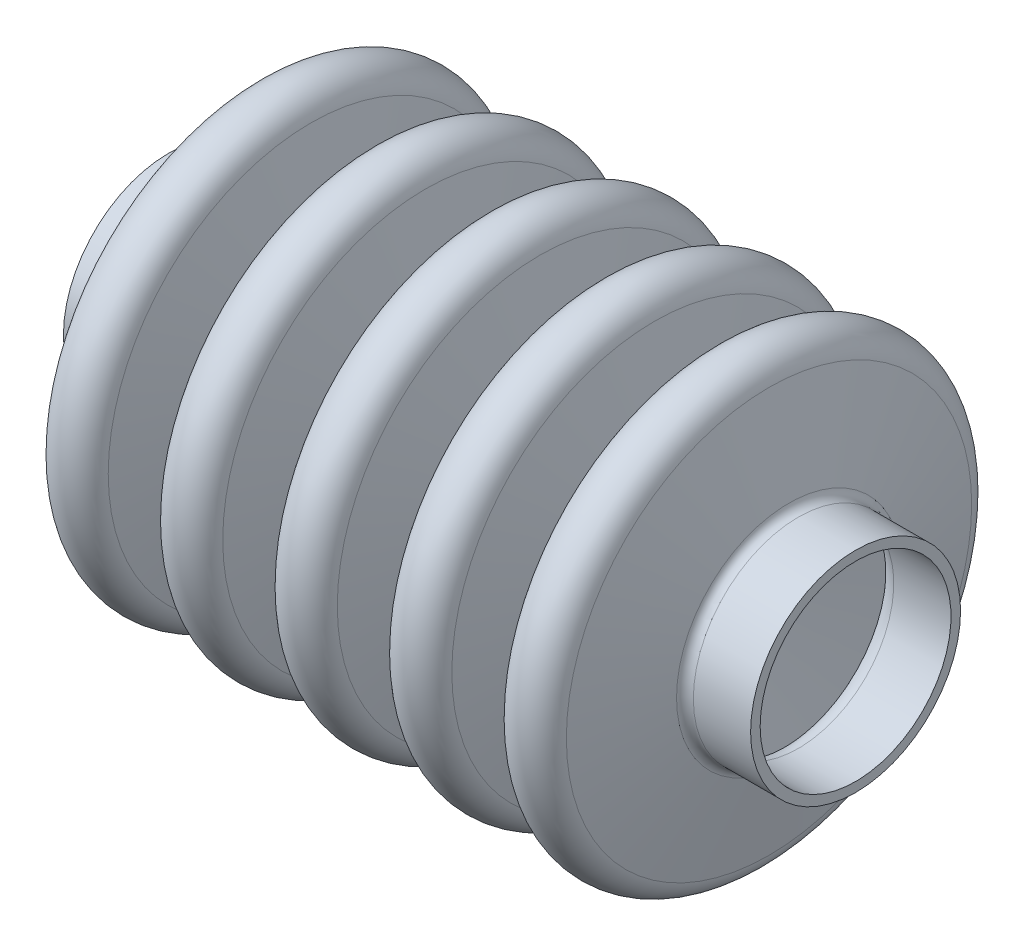
SolidWorks part; units mm, degrees
ref_plane "Front Plane" through (0, 0, 0) normal (0, 0, 1) x (1, 0, 0)
ref_plane "Top Plane" through (0, 0, 0) normal (0, 1, 0) x (1, 0, 0)
ref_plane "Right Plane" through (0, 0, 0) normal (1, 0, 0) x (0, 0, -1)
sketch "Sketch2" plane through (0, 0, 0) normal (0, 1, 0) x (1, 0, 0)
  line L0 (0, 0) -> (35.1605, 0) construction
  line L1 (0, 0) -> (0, 10) construction
  line L2 (0, 10) -> (-6, 10)
  line L3 (-12, 0) -> (-12, 10) construction
  line L4 (-7.9526, 11.5671) -> (-10.0474, 21.0162)
  line L5 (-16.0474, 11.5671) -> (-13.9526, 21.0162)
  line L6 (-19.9526, 11.5671) -> (-22.0474, 21.0162)
  line L7 (-28.0474, 11.5671) -> (-25.9526, 21.0162)
  line L8 (-31.9526, 11.5671) -> (-34.0474, 21.0162)
  line L9 (-40.0474, 11.5671) -> (-37.9526, 21.0162)
  line L10 (-43.9526, 11.5671) -> (-46.0474, 21.0162)
  line L11 (-52.0474, 11.5671) -> (-49.9526, 21.0162)
  line L12 (-55.9526, 11.5671) -> (-58.0474, 21.0162)
  line L13 (-64.0474, 11.5671) -> (-61.9526, 21.0162)
  line L14 (-6, 10) -> (-18, 10) construction
  line L15 (-66, 10) -> (-72, 10)
  line L16 (-54.9763, 11.7836) -> (-57.0711, 21.2327)
  line L17 (-65.0237, 11.7836) -> (-62.9289, 21.2327)
  line L18 (-66, 11) -> (-72, 11)
  line L19 (-42.9763, 11.7836) -> (-45.0711, 21.2327)
  line L20 (-53.0237, 11.7836) -> (-50.9289, 21.2327)
  line L21 (-30.9763, 11.7836) -> (-33.0711, 21.2327)
  line L22 (-41.0237, 11.7836) -> (-38.9289, 21.2327)
  line L23 (-18.9763, 11.7836) -> (-21.0711, 21.2327)
  line L24 (-29.0237, 11.7836) -> (-26.9289, 21.2327)
  line L25 (0, 11) -> (-6, 11)
  line L26 (-6.9763, 11.7836) -> (-9.0711, 21.2327)
  line L27 (-17.0237, 11.7836) -> (-14.9289, 21.2327)
  line L28 (-54, 10) -> (-54, 11)
  line L29 (-72, 10) -> (-72, 11)
  line L30 (-42, 10) -> (-42, 11)
  line L31 (-54, 10) -> (-54, 11)
  line L32 (-30, 10) -> (-30, 11)
  line L33 (-42, 10) -> (-42, 11)
  line L34 (-18, 10) -> (-18, 11)
  line L35 (-30, 10) -> (-30, 11)
  line L36 (0, 10) -> (0, 11)
  line L37 (-18, 10) -> (-18, 11)
  arc A0 (-6, 10) -> (-7.9526, 11.5671) centre (-6, 12) cw
  arc A1 (-10.0474, 21.0162) -> (-13.9526, 21.0162) centre (-12, 20.5833) ccw
  arc A2 (-18, 10) -> (-16.0474, 11.5671) centre (-18, 12) ccw
  arc A3 (-18, 10) -> (-19.9526, 11.5671) centre (-18, 12) cw
  arc A4 (-22.0474, 21.0162) -> (-25.9526, 21.0162) centre (-24, 20.5833) ccw
  arc A5 (-30, 10) -> (-28.0474, 11.5671) centre (-30, 12) ccw
  arc A6 (-30, 10) -> (-31.9526, 11.5671) centre (-30, 12) cw
  arc A7 (-34.0474, 21.0162) -> (-37.9526, 21.0162) centre (-36, 20.5833) ccw
  arc A8 (-42, 10) -> (-40.0474, 11.5671) centre (-42, 12) ccw
  arc A9 (-42, 10) -> (-43.9526, 11.5671) centre (-42, 12) cw
  arc A10 (-46.0474, 21.0162) -> (-49.9526, 21.0162) centre (-48, 20.5833) ccw
  arc A11 (-54, 10) -> (-52.0474, 11.5671) centre (-54, 12) ccw
  arc A12 (-54, 10) -> (-55.9526, 11.5671) centre (-54, 12) cw
  arc A13 (-58.0474, 21.0162) -> (-61.9526, 21.0162) centre (-60, 20.5833) ccw
  arc A14 (-66, 10) -> (-64.0474, 11.5671) centre (-66, 12) ccw
  arc A15 (-54, 11) -> (-54.9763, 11.7836) centre (-54, 12) cw
  arc A16 (-57.0711, 21.2327) -> (-62.9289, 21.2327) centre (-60, 20.5833) ccw
  arc A17 (-66, 11) -> (-65.0237, 11.7836) centre (-66, 12) ccw
  arc A18 (-42, 11) -> (-42.9763, 11.7836) centre (-42, 12) cw
  arc A19 (-45.0711, 21.2327) -> (-50.9289, 21.2327) centre (-48, 20.5833) ccw
  arc A20 (-54, 11) -> (-53.0237, 11.7836) centre (-54, 12) ccw
  arc A21 (-30, 11) -> (-30.9763, 11.7836) centre (-30, 12) cw
  arc A22 (-33.0711, 21.2327) -> (-38.9289, 21.2327) centre (-36, 20.5833) ccw
  arc A23 (-42, 11) -> (-41.0237, 11.7836) centre (-42, 12) ccw
  arc A24 (-18, 11) -> (-18.9763, 11.7836) centre (-18, 12) cw
  arc A25 (-21.0711, 21.2327) -> (-26.9289, 21.2327) centre (-24, 20.5833) ccw
  arc A26 (-30, 11) -> (-29.0237, 11.7836) centre (-30, 12) ccw
  arc A27 (-6, 11) -> (-6.9763, 11.7836) centre (-6, 12) cw
  arc A28 (-9.0711, 21.2327) -> (-14.9289, 21.2327) centre (-12, 20.5833) ccw
  arc A29 (-18, 11) -> (-17.0237, 11.7836) centre (-18, 12) ccw
  dimension "D2" = 2
  dimension "D1" = 10
  dimension "D3" = 6
  dimension "D4" = 12
  dimension "D5" = 12.5
  dimension "D7" = 12
  dimension "D8" = 6
  dimension "D9" = 1
  dimension "D6" = 5
revolve "Revolve1" add sketch "Sketch2" angle 360 about L0
